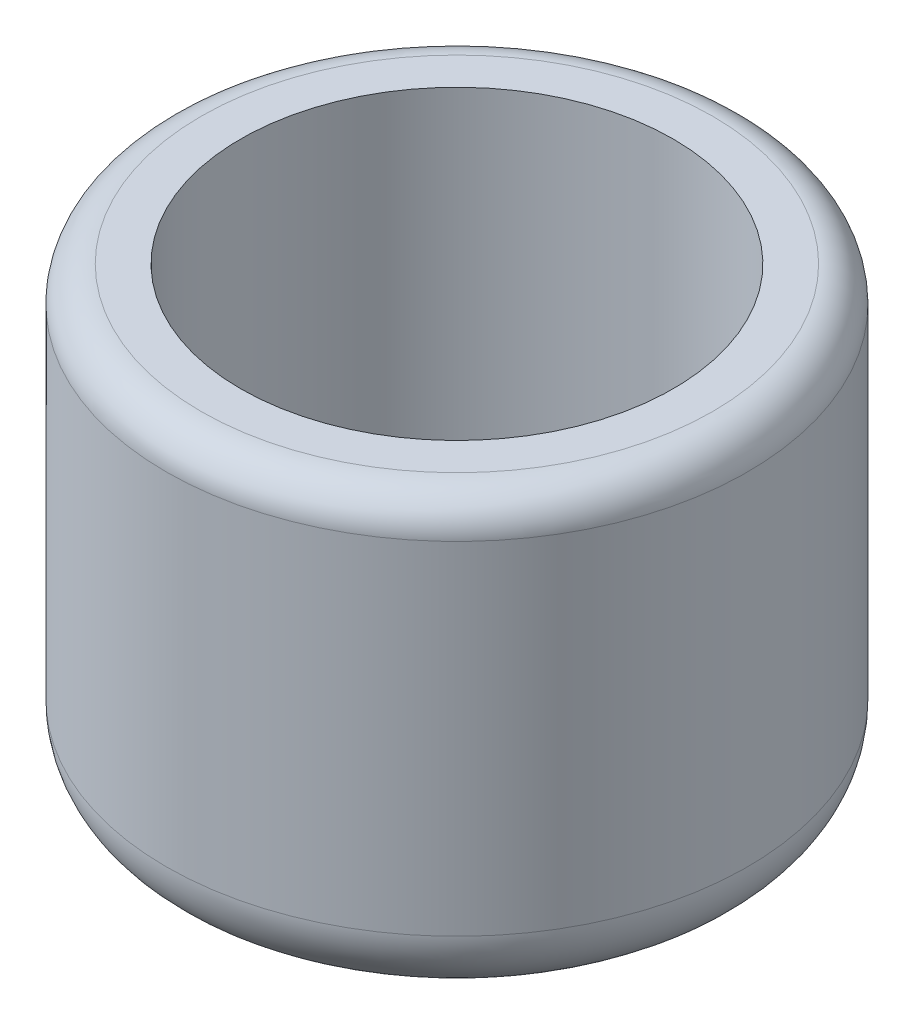
SolidWorks part; units mm, degrees
material "PVC Rigid"
ref_plane "Front Plane" through (0, 0, 0) normal (0, 0, 1) x (1, 0, 0)
ref_plane "Top Plane" through (0, 0, 0) normal (0, 1, 0) x (1, 0, 0)
ref_plane "Right Plane" through (0, 0, 0) normal (1, 0, 0) x (0, 0, -1)
sketch "Sketch1" plane through (0, 0, 0) normal (0, 1, 0) x (1, 0, 0)
  circle A0 centre (0, 0) radius 10.5791
  dimension "D1" = 21.1582
extrude "Boss-Extrude1" add sketch "Sketch1" along normal blind 16.256
sketch "Sketch2" plane through (0, 16.256, 0) normal (0, 1, 0) x (1, 0, 0)
  circle A0 centre (0, 0) radius 7.874
  dimension "D1" = 15.748
extrude "Cut-Extrude1" cut sketch "Sketch2" against normal blind 13.97
fillet "Fillet1" radius 1.27 1 edges at (0, 16.256, 10.5791)
fillet "Fillet2" radius 2.54 1 edges at (0, 0, 10.5791)
sketch "Sketch4" plane through (0, 2.286, 0) normal (0, 1, 0) x (1, 0, 0)
  circle A0 centre (0, 0) radius 1.143
  dimension "D1" = 2.286
extrude "Cut-Extrude2" cut sketch "Sketch4" against normal through all
